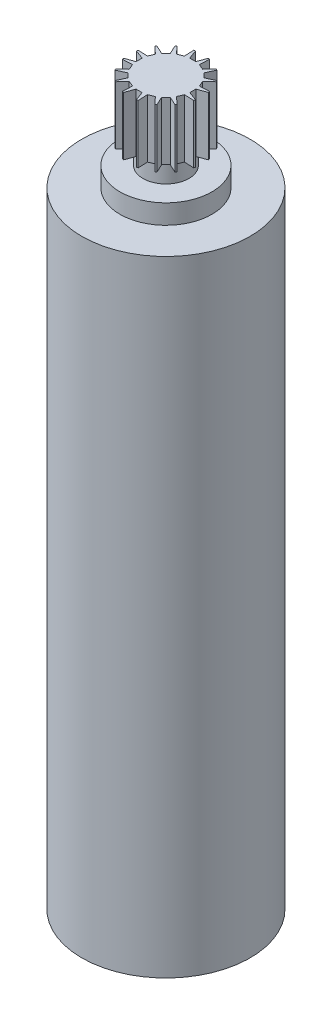
SolidWorks part; units mm, degrees
ref_plane "Front Plane" through (0, 0, 0) normal (0, 0, 1) x (1, 0, 0)
ref_plane "Top Plane" through (0, 0, 0) normal (0, 1, 0) x (1, 0, 0)
ref_plane "Right Plane" through (0, 0, 0) normal (1, 0, 0) x (0, 0, -1)
sketch "Sketch1" plane through (0, 0, 0) normal (0, 1, 0) x (1, 0, 0)
  circle A0 centre (0, 0) radius 10.9855
  dimension "D1" = 21.971
extrude "Boss-Extrude1" add sketch "Sketch1" along normal blind 81.534
sketch "Sketch2" plane through (0, 81.534, 0) normal (0, 1, 0) x (1, 0, 0)
  circle A0 centre (0, 0) radius 6.0071
  dimension "D1" = 12.0142
extrude "Boss-Extrude2" add sketch "Sketch2" along normal blind 2.54
sketch "Sketch3" plane through (0, 84.074, 0) normal (0, 1, 0) x (1, 0, 0)
  circle A0 centre (0, 0) radius 2.9972
  dimension "D1" = 5.9944
extrude "Boss-Extrude3" add sketch "Sketch3" along normal blind 2.54
sketch "Sketch4" plane through (0, 86.614, 0) normal (0, 1, 0) x (1, 0, 0)
  circle A0 centre (0, 0) radius 4.7625
extrude "Boss-Extrude4" add sketch "Sketch4" along normal blind 7.62
sketch "Sketch7" plane through (0, 94.234, 0) normal (0, 1, 0) x (1, 0, 0)
  line L0 (-0.8573, 4.7625) -> (0.8573, 4.7625)
  line L1 (0.8573, 4.7625) -> (0.3984, 3.5019)
  line L2 (0.3984, 3.5019) -> (-0.3984, 3.5019)
  line L3 (-0.3984, 3.5019) -> (-0.8573, 4.7625)
  line L4 (1.7082, 3.0829) -> (0.972, 3.3878)
  line L5 (2.6145, 4.0719) -> (1.7082, 3.0829)
  line L6 (1.0305, 4.728) -> (2.6145, 4.0719)
  line L7 (0.972, 3.3878) -> (1.0305, 4.728)
  line L8 (2.7579, 2.1945) -> (2.1945, 2.7579)
  line L9 (3.9738, 2.7614) -> (2.7579, 2.1945)
  line L10 (2.7614, 3.9738) -> (3.9738, 2.7614)
  line L11 (2.1945, 2.7579) -> (2.7614, 3.9738)
  line L12 (3.3878, 0.972) -> (3.0829, 1.7082)
  line L13 (4.728, 1.0305) -> (3.3878, 0.972)
  line L14 (4.0719, 2.6145) -> (4.728, 1.0305)
  line L15 (3.0829, 1.7082) -> (4.0719, 2.6145)
  line L16 (3.5019, -0.3984) -> (3.5019, 0.3984)
  line L17 (4.7625, -0.8572) -> (3.5019, -0.3984)
  line L18 (4.7625, 0.8573) -> (4.7625, -0.8572)
  line L19 (3.5019, 0.3984) -> (4.7625, 0.8573)
  line L20 (3.0829, -1.7082) -> (3.3878, -0.972)
  line L21 (4.0719, -2.6145) -> (3.0829, -1.7082)
  line L22 (4.728, -1.0305) -> (4.0719, -2.6145)
  line L23 (3.3878, -0.972) -> (4.728, -1.0305)
  line L24 (2.1945, -2.7579) -> (2.7579, -2.1945)
  line L25 (2.7614, -3.9738) -> (2.1945, -2.7579)
  line L26 (3.9738, -2.7614) -> (2.7614, -3.9738)
  line L27 (2.7579, -2.1945) -> (3.9738, -2.7614)
  line L28 (0.972, -3.3878) -> (1.7082, -3.0829)
  line L29 (1.0305, -4.728) -> (0.972, -3.3878)
  line L30 (2.6145, -4.0719) -> (1.0305, -4.728)
  line L31 (1.7082, -3.0829) -> (2.6145, -4.0719)
  line L32 (-0.3984, -3.5019) -> (0.3984, -3.5019)
  line L33 (-0.8572, -4.7625) -> (-0.3984, -3.5019)
  line L34 (0.8573, -4.7625) -> (-0.8572, -4.7625)
  line L35 (0.3984, -3.5019) -> (0.8573, -4.7625)
  line L36 (-1.7082, -3.0829) -> (-0.972, -3.3878)
  line L37 (-2.6145, -4.0719) -> (-1.7082, -3.0829)
  line L38 (-1.0305, -4.728) -> (-2.6145, -4.0719)
  line L39 (-0.972, -3.3878) -> (-1.0305, -4.728)
  line L40 (-2.7579, -2.1945) -> (-2.1945, -2.7579)
  line L41 (-3.9738, -2.7614) -> (-2.7579, -2.1945)
  line L42 (-2.7614, -3.9738) -> (-3.9738, -2.7614)
  line L43 (-2.1945, -2.7579) -> (-2.7614, -3.9738)
  line L44 (-3.3878, -0.972) -> (-3.0829, -1.7082)
  line L45 (-4.728, -1.0305) -> (-3.3878, -0.972)
  line L46 (-4.0719, -2.6145) -> (-4.728, -1.0305)
  line L47 (-3.0829, -1.7082) -> (-4.0719, -2.6145)
  line L48 (-3.5019, 0.3984) -> (-3.5019, -0.3984)
  line L49 (-4.7625, 0.8572) -> (-3.5019, 0.3984)
  line L50 (-4.7625, -0.8573) -> (-4.7625, 0.8572)
  line L51 (-3.5019, -0.3984) -> (-4.7625, -0.8573)
  line L52 (-3.0829, 1.7082) -> (-3.3878, 0.972)
  line L53 (-4.0719, 2.6145) -> (-3.0829, 1.7082)
  line L54 (-4.728, 1.0305) -> (-4.0719, 2.6145)
  line L55 (-3.3878, 0.972) -> (-4.728, 1.0305)
  line L56 (-2.1945, 2.7579) -> (-2.7579, 2.1945)
  line L57 (-2.7614, 3.9738) -> (-2.1945, 2.7579)
  line L58 (-3.9738, 2.7614) -> (-2.7614, 3.9738)
  line L59 (-2.7579, 2.1945) -> (-3.9738, 2.7614)
  line L60 (-0.972, 3.3878) -> (-1.7082, 3.0829)
  line L61 (-1.0305, 4.728) -> (-0.972, 3.3878)
  line L62 (-2.6145, 4.0719) -> (-1.0305, 4.728)
  line L63 (-1.7082, 3.0829) -> (-2.6145, 4.0719)
  circle A0 centre (0, 0) radius 4.7625 construction
  point P0 (0, 4.7625)
  point P8 (0, 4.7625)
  dimension "D1" = 70
  dimension "D2" = 70
  dimension "D3" = 1.7145
  dimension "D4" = 16
extrude "Cut-Extrude1" cut sketch "Sketch7" against normal blind 7.62
